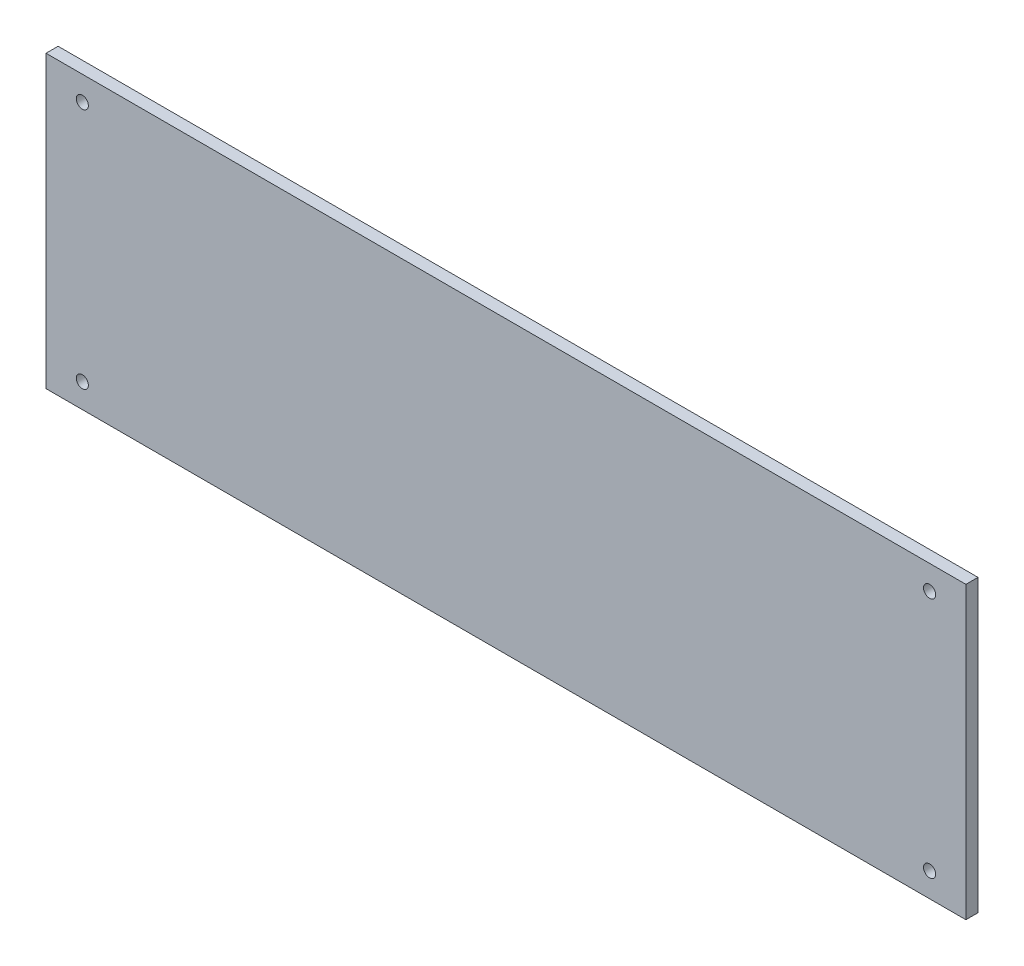
SolidWorks part; units mm, degrees
ref_plane "Front Plane" through (0, 0, 0) normal (0, 0, 1) x (1, 0, 0)
ref_plane "Top Plane" through (0, 0, 0) normal (0, 1, 0) x (1, 0, 0)
ref_plane "Right Plane" through (0, 0, 0) normal (1, 0, 0) x (0, 0, -1)
sketch "Sketch1" plane through (0, 0, 0) normal (0, 0, 1) x (1, 0, 0)
  line L1 (-241.3, -76.2) -> (241.3, -76.2)
  line L2 (-241.3, -76.2) -> (-241.3, 76.2)
  line L3 (-241.3, 76.2) -> (241.3, 76.2)
  line L4 (241.3, -76.2) -> (241.3, 76.2)
  line L5 (-241.3, -76.2) -> (241.3, 76.2) construction
  line L6 (-241.3, 76.2) -> (241.3, -76.2) construction
  point P0 (0, 0)
  dimension "D1" = 482.6
  dimension "D2" = 152.4
extrude "Boss-Extrude1" add sketch "Sketch1" along normal blind 6.35
sketch "Sketch2" plane through (0, 0, 6.35) normal (0, 0, 1) x (1, 0, 0)
  line L0 (-241.3, 76.2) -> (-241.3, -76.2) construction
  line L1 (-241.3, -76.2) -> (241.3, -76.2) construction
  circle A0 centre (-222.25, -63.5) radius 3.175
  dimension "D3" = 6.35
  dimension "D1" = 19.05
  dimension "D2" = 12.7
extrude "Cut-Extrude1" cut sketch "Sketch2" against normal through all
mirror "Mirror1" about plane through (0, 0, 0) normal (1, 0, 0) of "Cut-Extrude1" second plane through (0, 0, 0) second plane normal (0, 1, 0)
